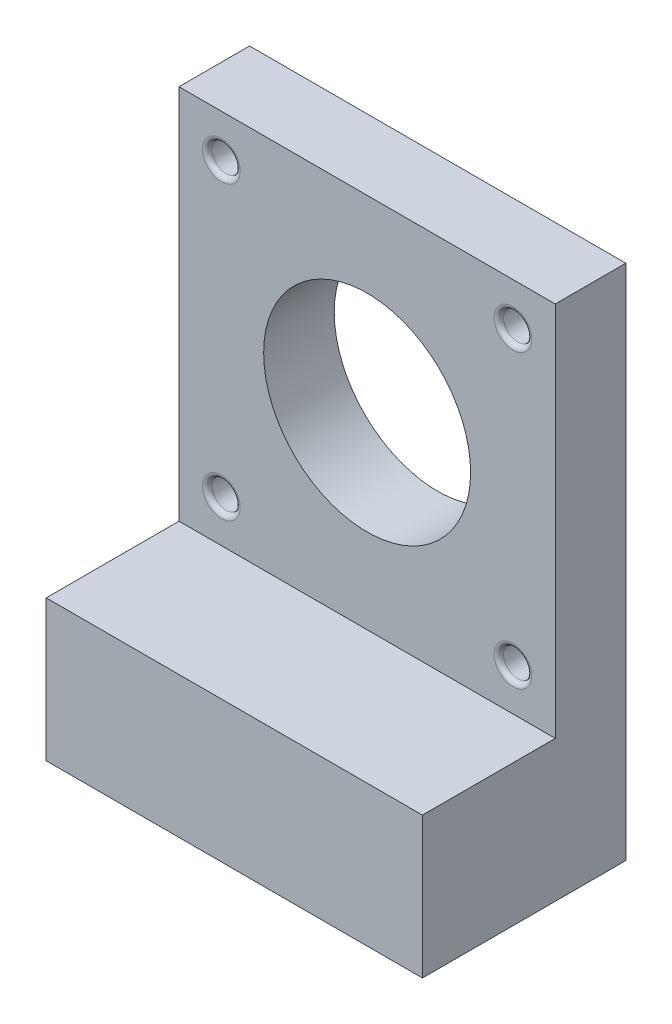
SolidWorks part; units mm, degrees
ref_plane "Front Plane" through (0, 0, 0) normal (0, 0, 1) x (1, 0, 0)
ref_plane "Top Plane" through (0, 0, 0) normal (0, 1, 0) x (1, 0, 0)
ref_plane "Right Plane" through (0, 0, 0) normal (1, 0, 0) x (0, 0, -1)
sketch "Sketch1" plane through (0, 0, 0) normal (0, 0, 1) x (1, 0, 0)
  line L1 (20, -30) -> (-20, -30)
  line L2 (20, -30) -> (20, 30)
  line L3 (20, 30) -> (-20, 30)
  line L4 (-20, -30) -> (-20, 30)
  line L5 (20, -30) -> (-20, 30) construction
  line L6 (20, 30) -> (-20, -30) construction
  circle A0 centre (0, 10) radius 11
  point P0 (0, 0)
  point P8 (0, 10)
  dimension "D4" = 22
  dimension "D1" = 60
  dimension "D2" = 40
extrude "Boss-Extrude1" add sketch "Sketch1" along normal blind 7.5
sketch "Sketch2" plane through (0, 0, 7.5) normal (0, 0, 1) x (1, 0, 0)
  line L0 (20, -30) -> (20, 30) construction
  line L1 (-20, -30) -> (20, -30)
  line L2 (-20, -30) -> (-20, -10)
  line L3 (-20, -10) -> (20, -10)
  line L4 (20, -30) -> (20, -10)
  dimension "D1" = 20
extrude "Boss-Extrude2" add sketch "Sketch2" along normal blind 14.12
sketch "Sketch4" plane through (0, 0, 0) normal (0, 0, -1) x (-1, 0, 0)
  line L1 (15.5, -5.5) -> (-15.5, -5.5) construction
  line L2 (15.5, -5.5) -> (15.5, 25.5) construction
  line L3 (15.5, 25.5) -> (-15.5, 25.5) construction
  line L4 (-15.5, -5.5) -> (-15.5, 25.5) construction
  line L5 (15.5, -5.5) -> (-15.5, 25.5) construction
  line L6 (15.5, 25.5) -> (-15.5, -5.5) construction
  circle A0 centre (-15.5, 25.5) radius 1.5
  circle A1 centre (15.5, 25.5) radius 1.5
  circle A2 centre (15.5, -5.5) radius 1.5
  circle A3 centre (-15.5, -5.5) radius 1.5
  point P0 (0, 10)
  dimension "D2" = 3
  dimension "D1" = 31
extrude "Cut-Extrude1" cut sketch "Sketch4" against normal through all
fillet "Fillet2" radius 0.5 8 edges at (14, -5.5, 0) (17, -5.5, 7.5) (-17, -5.5, 0) (-14, -5.5, 7.5) (-17, 25.5, 0) (-14, 25.5, 7.5) (14, 25.5, 0) (17, 25.5, 7.5)
sketch "Sketch5" plane through (0, 0, 0) normal (0, 0, -1) x (-1, 0, 0)
  line L0 (-20, -30) -> (-20, 30) construction
  line L1 (20, -30) -> (-20, -30)
  line L2 (20, -30) -> (20, -25)
  line L3 (20, -25) -> (-20, -25)
  line L4 (-20, -30) -> (-20, -25)
  point P7 (0, 10)
  dimension "D1" = 35
extrude "Cut-Extrude2" cut sketch "Sketch5" against normal through all
